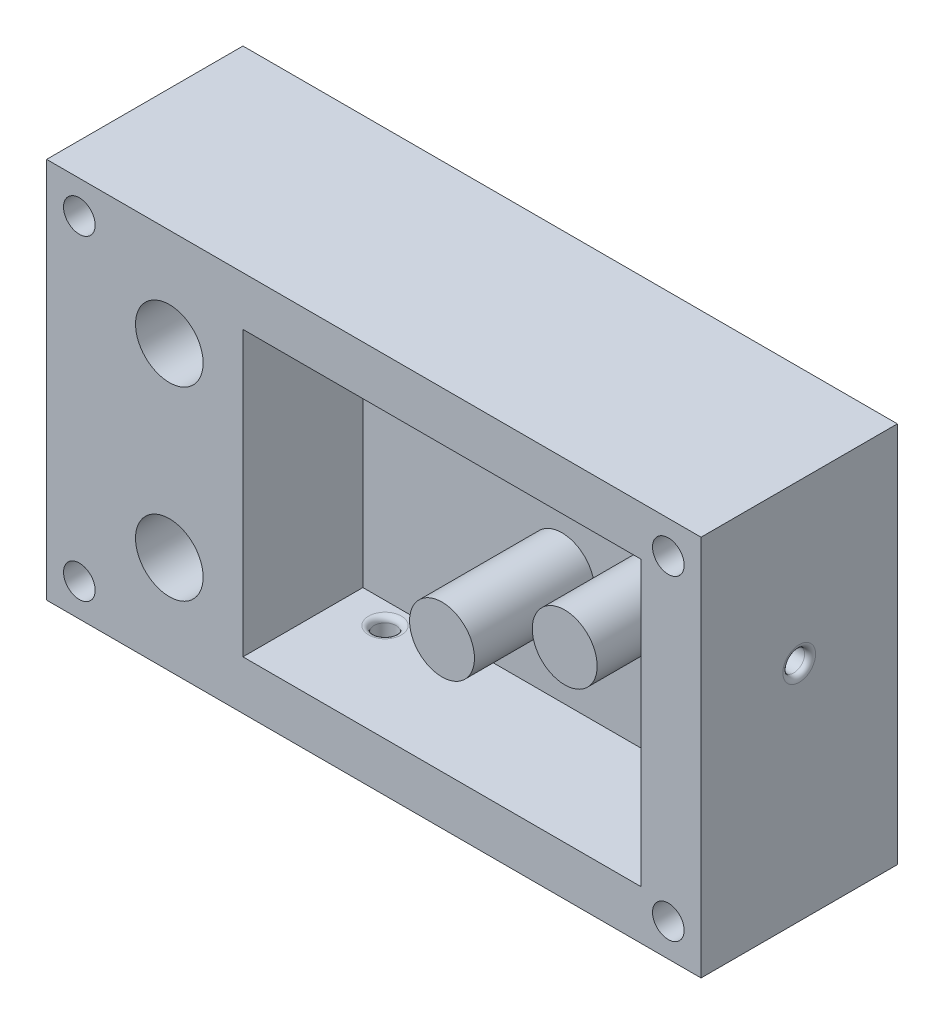
SolidWorks part; units mm, degrees
ref_plane "Front Plane" through (0, 0, 0) normal (0, 0, 1) x (1, 0, 0)
ref_plane "Top Plane" through (0, 0, 0) normal (0, 1, 0) x (1, 0, 0)
ref_plane "Right Plane" through (0, 0, 0) normal (1, 0, 0) x (0, 0, -1)
sketch "Sketch1" plane through (0, 0, 0) normal (0, 0, 1) x (1, 0, 0)
  line L1 (0, 0) -> (60, 0)
  line L2 (0, 0) -> (0, 35)
  line L3 (0, 35) -> (60, 35)
  line L4 (60, 0) -> (60, 35)
  dimension "D1" = 60
  dimension "D2" = 35
extrude "Boss-Extrude1" add sketch "Sketch1" along normal blind 18 contours L2 L1 L4 L3
sketch "Sketch2" plane through (0, 0, 18) normal (0, 0, 1) x (1, 0, 0)
  line L0 (0, 32.5) -> (60, 32.5) construction
  line L1 (0, 0) -> (0, 35) construction
  line L2 (60, 0) -> (60, 35) construction
  line L3 (0, 2.5) -> (60, 2.5) construction
  line L4 (2.5, 35) -> (2.5, 0) construction
  line L5 (0, 35) -> (60, 35) construction
  line L6 (0, 0) -> (60, 0) construction
  line L7 (57.5, 35) -> (57.5, 0) construction
  line L8 (20, 35) -> (20, 0) construction
  line L9 (11.25, 35) -> (11.25, 0) construction
  circle A0 centre (11.25, 26) radius 3.1
  circle A1 centre (11.25, 9) radius 3.1
  dimension "D7" = 6.2
  dimension "D8" = 17
  dimension "D1" = 2.5
  dimension "D2" = 2.5
  dimension "D3" = 2.5
  dimension "D4" = 2.5
  dimension "D5" = 20
  dimension "D6" = 8.75
  dimension "D9" = 9
extrude "Cut-Extrude1" cut sketch "Sketch2" against normal blind 18
sketch "Sketch3" plane through (0, 0, 18) normal (0, 0, 1) x (1, 0, 0)
  line L0 (0, 32) -> (60, 32) construction
  line L1 (0, 0) -> (0, 35) construction
  line L2 (60, 0) -> (60, 35) construction
  line L3 (3, 35) -> (3, 0) construction
  line L4 (0, 35) -> (60, 35) construction
  line L5 (0, 0) -> (60, 0) construction
  line L6 (0, 3) -> (60, 3) construction
  line L7 (57, 35) -> (57, 0) construction
  line L8 (18, 35) -> (18, 0) construction
  line L10 (18, 4.5) -> (54.5, 4.5)
  line L11 (18, 4.5) -> (18, 30.5)
  line L12 (18, 30.5) -> (54.5, 30.5)
  line L13 (54.5, 4.5) -> (54.5, 30.5)
  circle A0 centre (3, 32) radius 1.45
  circle A1 centre (57, 32) radius 1.45
  circle A2 centre (57, 3) radius 1.45
  circle A3 centre (3, 3) radius 1.45
  dimension "D6" = 2.9
  dimension "D1" = 3
  dimension "D2" = 3
  dimension "D3" = 3
  dimension "D4" = 3
  dimension "D5" = 18
  dimension "D7" = 1.5
  dimension "D8" = 1.5
  dimension "D9" = 2.5
extrude "Cut-Extrude2" cut sketch "Sketch3" against normal blind 11
sketch "Sketch4" plane through (0, 0, 7) normal (0, 0, 1) x (1, 0, 0)
  line L0 (18, 17.5) -> (54.5, 17.5) construction
  line L1 (18, 30.5) -> (18, 4.5) construction
  line L2 (54.5, 4.5) -> (54.5, 30.5) construction
  line L3 (18, 15) -> (54.5, 15) construction
  line L4 (54.5, 4.5) -> (54.5, 30.5) construction
  line L6 (18, 20) -> (54.5, 20) construction
  line L7 (18, 30.5) -> (18, 4.5) construction
  circle A1 centre (36.25, 15) radius 2.975
  circle A3 centre (47.5, 20) radius 2.975
  point P20 (0, 0)
  dimension "D2" = 2.5
  dimension "D1" = 2.5
extrude "Boss-Extrude2" add sketch "Sketch4" along normal blind 11
sketch "Sketch6" plane through (60, 0, 0) normal (1, 0, 0) x (0, 0, -1)
  line L0 (-9, 35) -> (-9, 0) construction
  line L1 (-18, 35) -> (0, 35) construction
  line L2 (-18, 0) -> (0, 0) construction
  line L3 (-18, 20.475) -> (0, 20.475) construction
  line L4 (-18, 0) -> (-18, 35) construction
  line L5 (0, 0) -> (0, 35) construction
  circle A0 centre (-9, 20.475) radius 1
  dimension "D1" = 20.475
extrude "Cut-Extrude3" cut sketch "Sketch6" against normal blind 5.8
sketch "Sketch8" plane through (0, 0, 0) normal (0, -1, 0) x (1, 0, 0)
  line L0 (0, 9) -> (60, 9) construction
  line L1 (0, 18) -> (0, 0) construction
  line L2 (60, 18) -> (60, 0) construction
  line L3 (22.025, 18) -> (22.025, 0) construction
  line L4 (0, 18) -> (60, 18) construction
  line L5 (0, 0) -> (60, 0) construction
  circle A0 centre (22.025, 9) radius 1
  dimension "D1" = 37.975
extrude "Cut-Extrude4" cut sketch "Sketch8" against normal blind 5.8
fillet "Fillet2" radius 0.5 4 edges at (60, 20.475, 8) (54.5, 20.475, 8) (22.025, 4.5, 8) (22.025, 0, 8)
